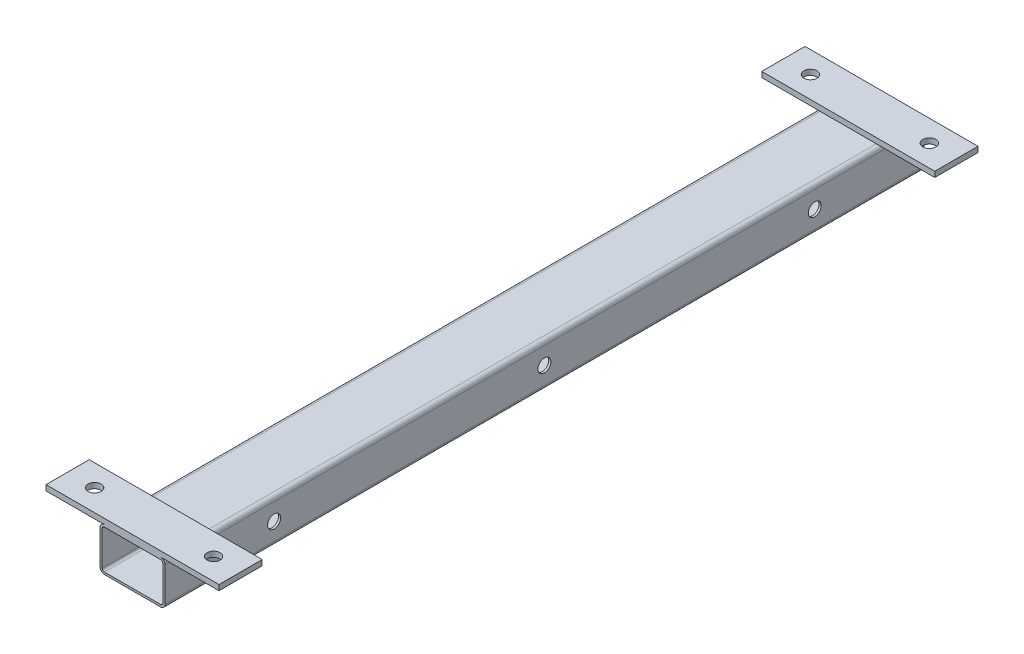
SolidWorks part; units mm, degrees
ref_plane "Płaszczyzna przednia" through (0, 0, 0) normal (0, 0, 1) x (1, 0, 0)
ref_plane "Płaszczyzna górna" through (0, 0, 0) normal (0, 1, 0) x (1, 0, 0)
ref_plane "Płaszczyzna prawa" through (0, 0, 0) normal (1, 0, 0) x (0, 0, -1)
sketch "Szkic1" plane through (0, 0, 0) normal (0, 0, 1) x (1, 0, 0)
  line L0 (0, 4) -> (0, 36)
  line L1 (4, 40) -> (56, 40)
  line L2 (60, 36) -> (60, 4)
  line L3 (56, 0) -> (4, 0)
  line L4 (2, 4) -> (2, 36)
  line L5 (4, 38) -> (56, 38)
  line L6 (58, 36) -> (58, 4)
  line L7 (56, 2) -> (4, 2)
  arc A0 (60, 4) -> (56, 0) centre (56, 4) cw
  arc A1 (60, 36) -> (56, 40) centre (56, 36) ccw
  arc A2 (0, 36) -> (4, 40) centre (4, 36) cw
  arc A3 (0, 4) -> (4, 0) centre (4, 4) ccw
  arc A4 (2, 36) -> (4, 38) centre (4, 36) cw
  arc A5 (58, 36) -> (56, 38) centre (56, 36) ccw
  arc A6 (58, 4) -> (56, 2) centre (56, 4) cw
  arc A7 (2, 4) -> (4, 2) centre (4, 4) ccw
  point P13 (0, 0)
  dimension "D1" = 4
  dimension "D3" = 40
  dimension "D4" = 60
  dimension "D2" = 2
extrude "Dodanie-wyciągnięcie1" add sketch "Szkic1" along normal blind 702
sketch "Szkic2" plane through (0, 40, 0) normal (0, 1, 0) x (1, 0, 0)
  line L0 (0, 0) -> (-50, 0)
  line L1 (-50, 0) -> (-50, -40)
  line L2 (-50, -40) -> (110, -40)
  line L3 (110, -40) -> (110, 0)
  line L4 (110, 0) -> (0, 0)
  line L5 (-50, -20) -> (110, -20) construction
  line L6 (-50, -20) -> (-25, -20) construction
  line L7 (110, -20) -> (85, -20) construction
  line L8 (0, 0) -> (0, -351) construction
  circle A0 centre (-25, -20) radius 6
  circle A1 centre (85, -20) radius 6
  dimension "D6" = 12
  dimension "D7" = 12
  dimension "D1" = 40
  dimension "D2" = 164.9242
  dimension "D3" = 110
  dimension "D4" = 25
  dimension "D5" = 25
  dimension "D8" = 351
ref_plane "Płaszczyzna1" through (0, 0, 351) normal (0, 0, -1) x (-1, 0, 0)
extrude "Dodanie-wyciągnięcie2" add sketch "Szkic2" along normal blind 5
mirror "Lustro1" about plane through (0, 0, 351) normal (0, 0, -1) of "Dodanie-wyciągnięcie2"
sketch "Szkic4" plane through (60, 0, 0) normal (1, 0, 0) x (0, 0, -1)
  line L0 (0, 0) -> (0, 20) construction
  line L1 (0, 4) -> (0, 36) construction
  line L2 (0, 20) -> (-101, 20) construction
  line L3 (-101, 20) -> (-351, 20) construction
  circle A0 centre (-101, 20) radius 6
  circle A1 centre (-351, 20) radius 6
  circle A2 centre (-601, 20) radius 6
  dimension "D1" = 3
  dimension "D4" = 12
  dimension "D2" = 250
  dimension "D3" = 102.9612
extrude "Wytnij-wyciągnięcie1" cut sketch "Szkic4" against normal blind 65
